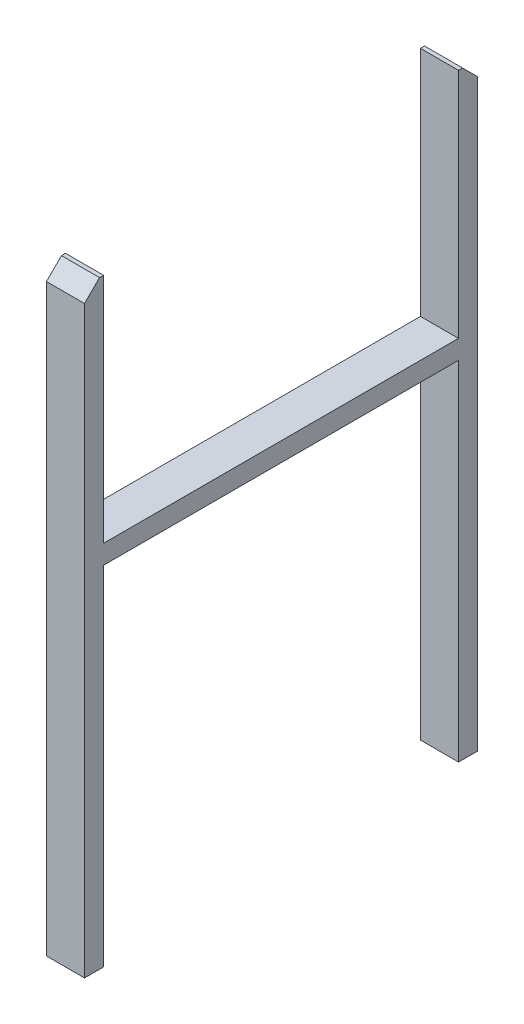
SolidWorks part; units mm, degrees
ref_plane "Alzado" through (0, 0, 0) normal (0, 0, 1) x (1, 0, 0)
ref_plane "Planta" through (0, 0, 0) normal (0, 1, 0) x (1, 0, 0)
ref_plane "Vista lateral" through (0, 0, 0) normal (1, 0, 0) x (0, 0, -1)
sketch "Croquis2" plane through (0, 0, 0) normal (0, 1, 0) x (1, 0, 0)
  line L0 (0, 0) -> (0, -25.4)
  line L1 (0, 0) -> (50.8, 0)
  line L2 (50.8, 0) -> (50.8, -25.4)
  line L3 (0, -25.4) -> (50.8, -25.4)
  line L4 (0, 499.4) -> (50.8, 499.4)
  line L5 (50.8, 474) -> (50.8, 499.4)
  line L6 (0, 474) -> (50.8, 474)
  line L7 (0, 474) -> (0, 499.4)
  line L9 (0, 0) -> (0, 474) construction
  line L10 (0, 237) -> (123.559, 237) construction
  dimension "D1" = 50.8
  dimension "D2" = 25.4
  dimension "D4" = 237
extrude "Saliente-Extruir1" add sketch "Croquis2" along normal blind 800
sketch "Croquis3" plane through (0, 0, -474) normal (0, 0, 1) x (1, 0, 0)
  line L0 (0, 800) -> (0, 0) construction
  line L1 (0, 490) -> (50.8, 490)
  line L2 (0, 490) -> (0, 464.6)
  line L3 (0, 464.6) -> (50.8, 464.6)
  line L4 (50.8, 490) -> (50.8, 464.6)
  line L5 (50.8, 800) -> (50.8, 0) construction
  line L6 (0, 800) -> (50.8, 800) construction
  dimension "D1" = 25.4
  dimension "D2" = 310
extrude "Saliente-Extruir2" add sketch "Croquis3" along normal up to surface (474 mm away) up to face at (25.4, 400, 0)
chamfer "Chaflán1" distance 20 angle 45 2 edges at (25.4, 800, 25.4) (25.4, 800, -499.4)
